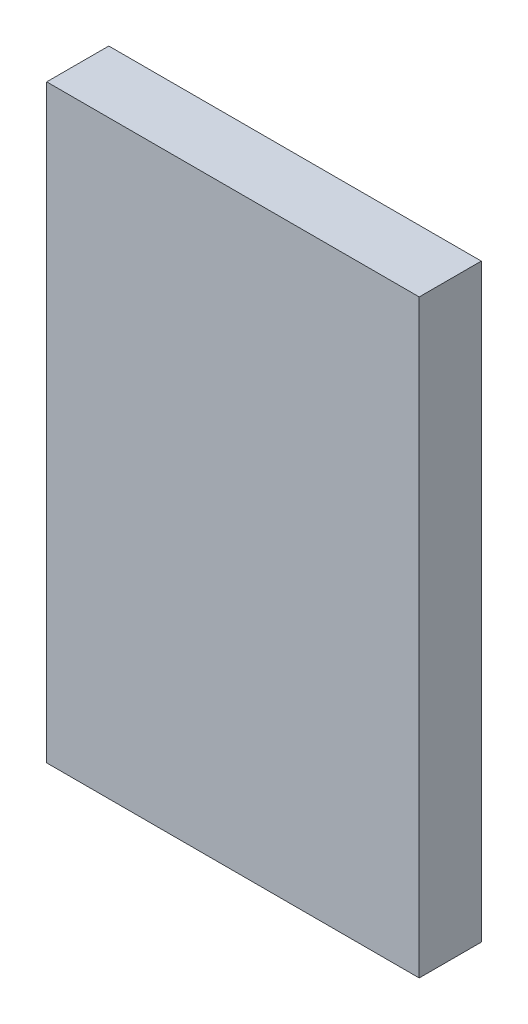
SolidWorks part; units mm, degrees
ref_plane "Front Plane" through (0, 0, 0) normal (0, 0, 1) x (1, 0, 0)
ref_plane "Top Plane" through (0, 0, 0) normal (0, 1, 0) x (1, 0, 0)
ref_plane "Right Plane" through (0, 0, 0) normal (1, 0, 0) x (0, 0, -1)
sketch "Sketch1" plane through (0, 0, 0) normal (0, 0, 1) x (1, 0, 0)
  line L1 (12, 19) -> (-12, 19)
  line L2 (12, 19) -> (12, -19)
  line L3 (12, -19) -> (-12, -19)
  line L4 (-12, 19) -> (-12, -19)
  line L5 (12, 19) -> (-12, -19) construction
  line L6 (12, -19) -> (-12, 19) construction
  point P0 (0, 0)
  dimension "D1" = 24
  dimension "D2" = 38
extrude "Boss-Extrude1" add sketch "Sketch1" along normal blind 4
